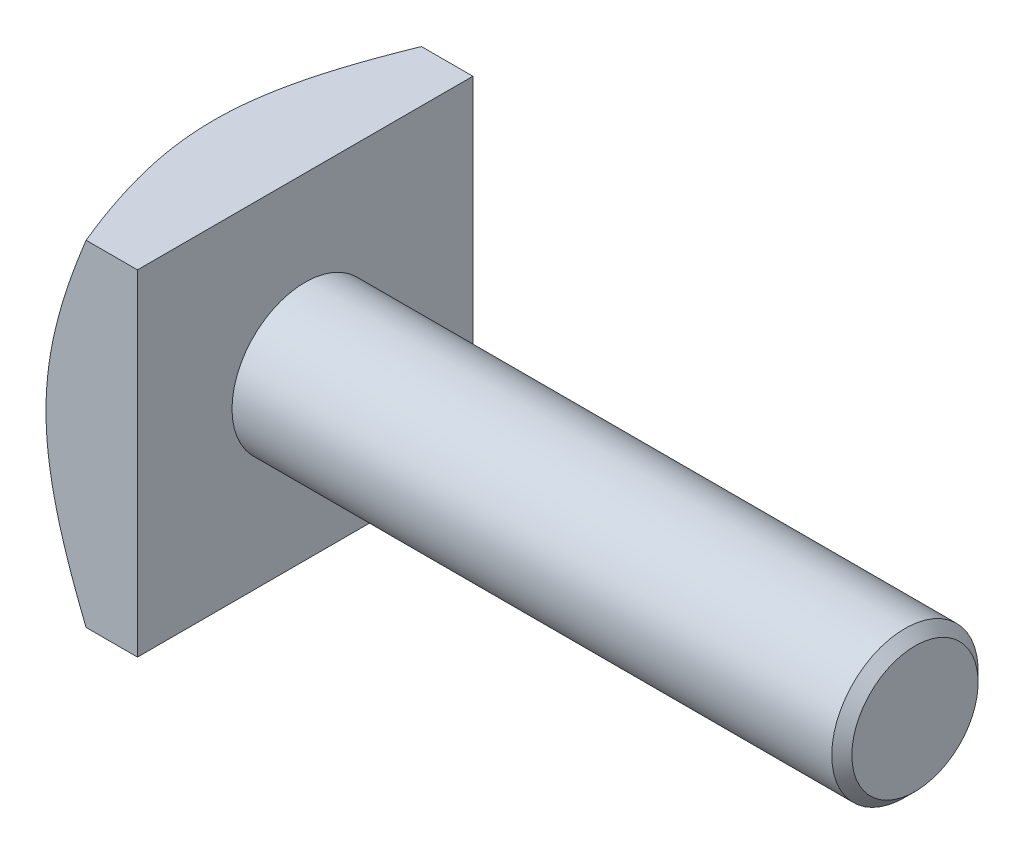
SolidWorks part; units mm, degrees
extrude "BaseHead" add sketch "Sketch1" along normal blind 15
sketch "Sketch1" plane through (0, 0, 0) normal (1, 0, 0) x (0, 0, -1)
  line L0 (27.5, 27.5) -> (27.5, -27.5)
  line L1 (-27.5, 27.5) -> (-27.5, -27.5)
  line L2 (0, 0) -> (22.2214, 0) construction
  line L3 (0, 0) -> (0, 20.1834) construction
  line L4 (-27.5, 27.5) -> (27.5, 27.5)
  line L5 (-27.5, -27.5) -> (27.5, -27.5)
  dimension "Width_flats" = 55
ref_plane "Plane1" through (0, 0, 0) normal (0, 0, 1) x (1, 0, 0)
ref_plane "Plane2" through (0, 0, 0) normal (0, 1, 0) x (1, 0, 0)
ref_plane "Plane3" through (0, 0, 0) normal (1, 0, 0) x (0, 0, -1)
sketch "BodySke" plane through (0, 0, 0) normal (0, 0, 1) x (1, 0, 0)
  line L0 (0, 27.5) -> (0, -27.5) construction
  line L1 (0, 0) -> (115, 0)
  line L2 (0, 0) -> (0, 12)
  line L3 (0, 12) -> (113.352, 12)
  line L4 (115, 0) -> (115, 10.352)
  line L6 (115, 10.352) -> (113.352, 12)
  line L7 (0, 0) -> (96.52, 0) construction
  line L8 (115, -10.352) -> (113.352, -12) construction
  line L9 (0, -12) -> (113.352, -12) construction
  line L10 (18, 15.24) -> (18, -1.27) construction
  line L11 (61, 15.24) -> (61, -1.27) construction
  line L12 (15, 27.5) -> (15, -27.5) construction
  line L13 (15, 27.5) -> (15, -27.5) construction
  dimension "Length" = 100
  dimension "Diameter" = 24
  dimension "Advance" = 3
revolve "BaseBody" add sketch "BodySke"
cosmetic thread "ThreadCosmetic" [suppressed]
fillet "HeadFillet" [suppressed] radius 0.8
sketch "Sketch3" plane through (0, 0, 0) normal (0, 0, 1) x (1, 0, 0)
  line L0 (0, 27.5) -> (8.0829, 41.5)
  line L2 (8.0829, 41.5) -> (8.0829, 42.5)
  line L3 (8.0829, 42.5) -> (-1, 42.5)
  line L4 (-1, 42.5) -> (-1, 27.5)
  line L5 (-1, 27.5) -> (0, 27.5)
  line L6 (0, 0) -> (99.06, 0) construction
  line L8 (15, 27.5) -> (0, 27.5) construction
  line L9 (0, 27.5) -> (0, -27.5) construction
  dimension "D2" = 15
  dimension "D3" = 1
  dimension "D4" = 1
  dimension "Head_ch_ang" = 30
revolve "HeadChamfer" cut sketch "Sketch3" angle 360 about L6
sketch "ThdSchSke" plane through (0, 0, 0) normal (0, 0, 1) x (1, 0, 0)
  line L0 (61, -10.352) -> (59.8461, -12)
  line L1 (61, -10.352) -> (62.1539, -12)
  line L2 (62.1539, -12) -> (62.1539, -15)
  line L3 (-3.175, 0) -> (5.1513, 0) construction
  line L5 (62.1539, -15) -> (59.8461, -15)
  line L6 (59.8461, -15) -> (59.8461, -12)
  dimension "Thread_minor" = 20.704
  dimension "Diameter" = 24
  dimension "Start" = 61
revolve "ThreadSchematic" [suppressed] cut sketch "ThdSchSke" angle 360 about L3
pattern_linear "ThdSchPat" [suppressed]
equation "\"Thread_minor@ThreadCosmetic\" = \"Minor_dia@BodySke\""
equation "\"Thread_length@ThreadCosmetic\" = ((sgn( (\"Length@BodySke\" - \"Advance@BodySke\" * 2 ) - \"Thread_nom@BodySke\" )-1)*( (\"Length@BodySke\" - \"Advance@BodySke\" * 2 ) - \"Thread_nom@BodySke\" ))/-2+ \"Thread_nom@BodySke\""
equation "\"Thread_minor@ThdSchSke\" = \"Minor_dia@BodySke\""
equation "\"Diameter@ThdSchSke\" = \"Diameter@BodySke\""
equation "\"Overcut@ThdSchSke\" = \"Diameter@BodySke\" * 1.25"
equation "\"Start@ThdSchSke\" = \"Head_ht@BaseHead\" + \"Length@BodySke\" - \"Thread_length@ThreadCosmetic\"  '---Non-countersunk---"
equation "\"Num_threads@ThdSchPat\" = int( \"Thread_length@ThreadCosmetic\" / \"Advance@BodySke\" + 0.999 )  + 1"
equation "\"Advance@ThdSchPat\" = \"Thread_length@ThreadCosmetic\" /  (\"Num_threads@ThdSchPat\" - 1) 'relax it"
equation "\"Num_threads@ThdSchPat\" = \"Num_threads@ThdSchPat\" - sgn( \"Num_threads@ThdSchPat\" - 1) '---chamfered tips only---"
